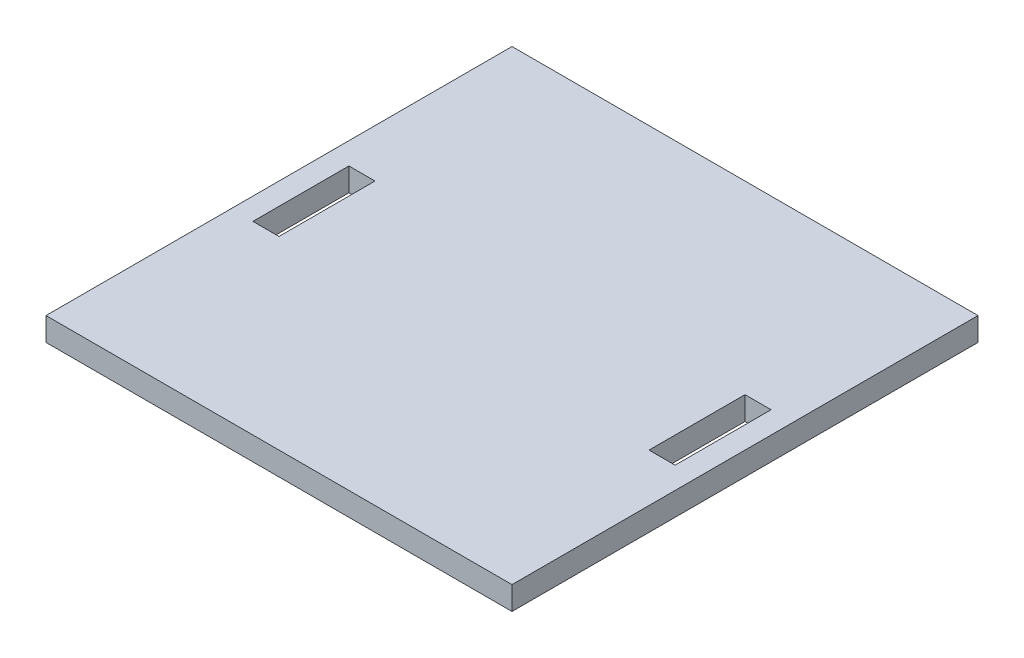
SolidWorks part; units mm, degrees
ref_plane "Спереди" through (0, 0, 0) normal (0, 0, 1) x (1, 0, 0)
ref_plane "Сверху" through (0, 0, 0) normal (0, 1, 0) x (1, 0, 0)
ref_plane "Справа" through (0, 0, 0) normal (1, 0, 0) x (0, 0, -1)
sketch "Sketch1" plane through (0, 0, 0) normal (0, 1, 0) x (1, 0, 0)
  line L0 (50, 0) -> (50, -100) construction
  line L1 (0, 0) -> (100, 0)
  line L2 (0, 0) -> (0, -100)
  line L3 (0, -100) -> (100, -100)
  line L4 (100, 0) -> (100, -100)
  line L13 (4.7, -39.7) -> (4.7, -60.3)
  line L14 (4.7, -60.3) -> (10.3, -60.3)
  line L15 (10.3, -39.7) -> (10.3, -60.3)
  line L16 (4.7, -39.7) -> (10.3, -39.7)
  line L17 (95.3, -39.7) -> (95.3, -60.3)
  line L18 (95.3, -60.3) -> (89.7, -60.3)
  line L19 (89.7, -39.7) -> (89.7, -60.3)
  line L20 (95.3, -39.7) -> (89.7, -39.7)
  dimension "D1" = 100
  dimension "D2" = 100
extrude "Boss-Extrude1" add sketch "Sketch1" along normal blind 5
